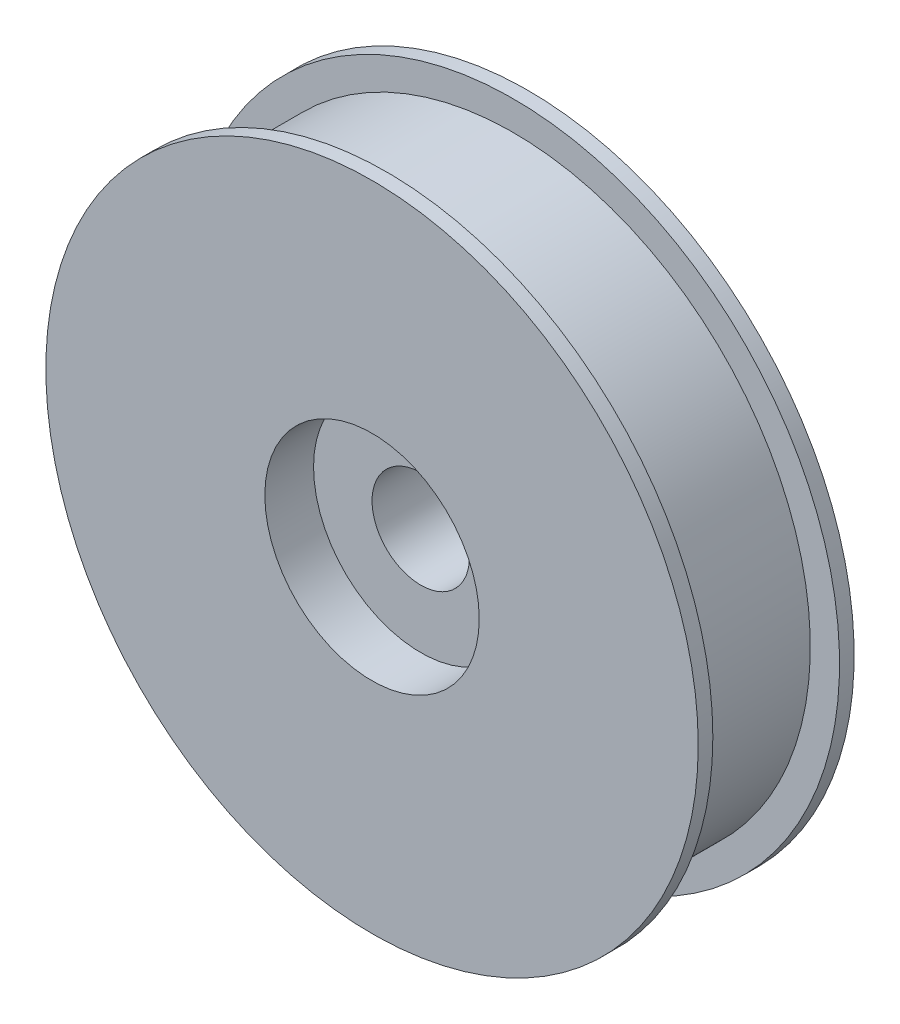
SolidWorks part; units mm, degrees
material "SKD11淬火HRC56-60"
ref_plane "前基準面" through (0, 0, 0) normal (0, 0, 1) x (1, 0, 0)
ref_plane "上基準面" through (0, 0, 0) normal (0, 1, 0) x (1, 0, 0)
ref_plane "右基準面" through (0, 0, 0) normal (1, 0, 0) x (0, 0, -1)
sketch "草图1" plane through (0, 0, 0) normal (0, 0, 1) x (1, 0, 0)
  circle A0 centre (0, 0) radius 30.47
  dimension "D1" = 60.94
extrude "凸台-拉伸1" add sketch "草图1" along normal blind 13
sketch "草图2" plane through (0, 0, 13) normal (0, 0, 1) x (1, 0, 0)
  circle A0 centre (0, 0) radius 33.47
  circle A1 centre (0, 0) radius 30.47 construction
  dimension "D1" = 3
extrude "凸台-拉伸2" add sketch "草图2" along normal blind 1.5
sketch "草图3" plane through (0, 0, 0) normal (0, 0, -1) x (-1, 0, 0)
  circle A0 centre (0, 0) radius 33.47
  circle A1 centre (0, 0) radius 30.47 construction
  dimension "D1" = 3
extrude "凸台-拉伸3" add sketch "草图3" along normal blind 1.5
sketch "草图4" plane through (0, 0, 14.5) normal (0, 0, 1) x (1, 0, 0)
  circle A0 centre (0, 0) radius 5
  dimension "D1" = 10
extrude "切除-拉伸1" cut sketch "草图4" against normal through all
sketch "草图5" plane through (0, 0, 14.5) normal (0, 0, 1) x (1, 0, 0)
  circle A0 centre (0, 0) radius 11
  dimension "D1" = 22
extrude "切除-拉伸2" cut sketch "草图5" against normal blind 5
